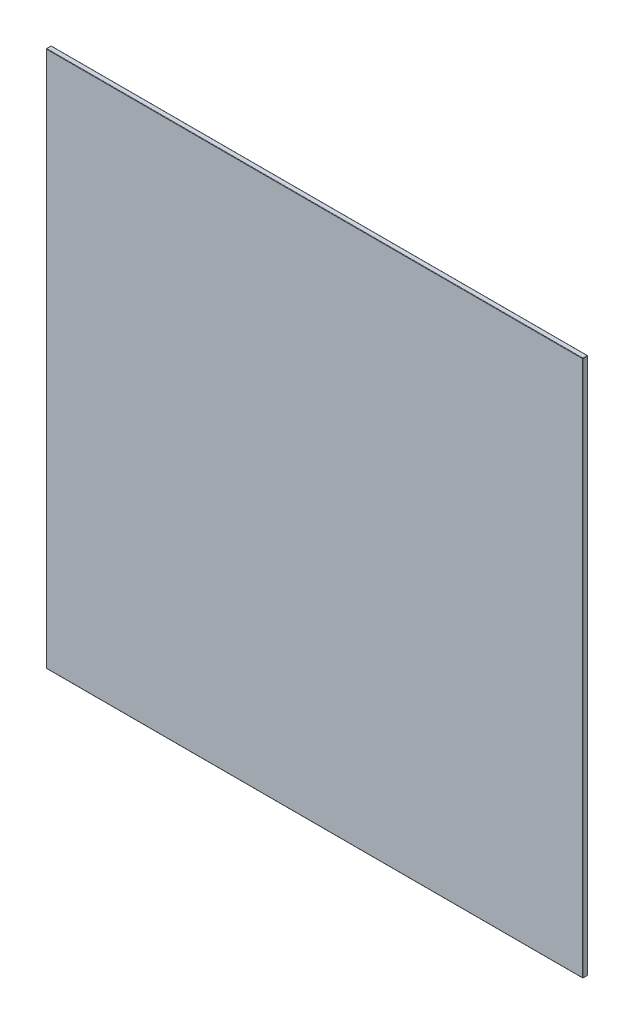
SolidWorks part; units mm, degrees
material "Glass"
ref_plane "Front Plane" through (0, 0, 0) normal (0, 0, 1) x (1, 0, 0)
ref_plane "Top Plane" through (0, 0, 0) normal (0, 1, 0) x (1, 0, 0)
ref_plane "Right Plane" through (0, 0, 0) normal (1, 0, 0) x (0, 0, -1)
sketch "Sketch1" plane through (0, 0, 0) normal (0, 0, 1) x (1, 0, 0)
  line L1 (-160, -160) -> (160, -160)
  line L2 (-160, -160) -> (-160, 160)
  line L3 (-160, 160) -> (160, 160)
  line L4 (160, -160) -> (160, 160)
  line L5 (-160, -160) -> (160, 160) construction
  line L6 (-160, 160) -> (160, -160) construction
  point P0 (0, 0)
  dimension "D1" = 320
  dimension "D2" = 320
extrude "Boss-Extrude1" add sketch "Sketch1" along normal blind 3
fillet "Fillet1" radius 0.25 12 edges at (0, 160, 3) (0, 160, 0) (160, 0, 3) (160, 160, 1.5) (160, 0, 0) (-160, 160, 1.5) (-160, 0, 3) (-160, 0, 0) (-160, -160, 1.5) (0, -160, 3) (160, -160, 1.5) (0, -160, 0)
